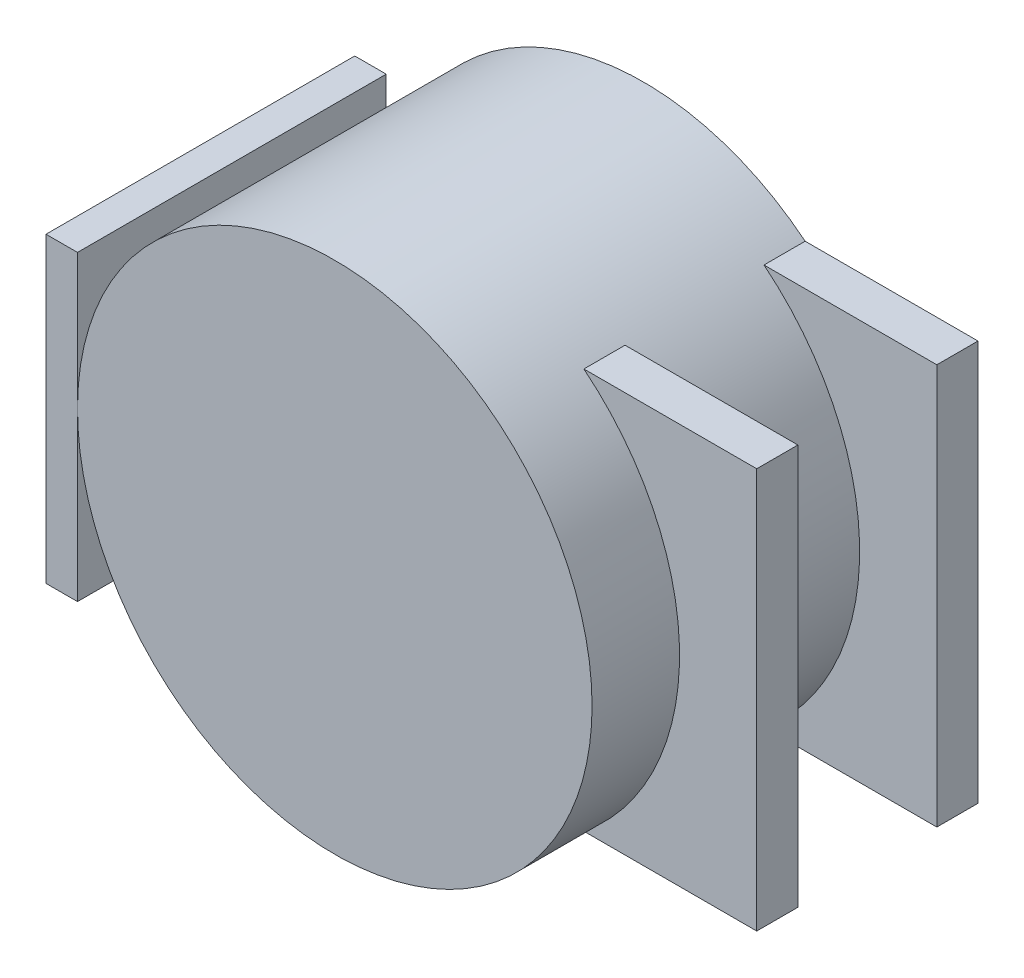
SolidWorks part; units mm, degrees
ref_plane "前视基准面" through (0, 0, 0) normal (0, 0, 1) x (1, 0, 0)
ref_plane "上视基准面" through (0, 0, 0) normal (0, 1, 0) x (1, 0, 0)
ref_plane "右视基准面" through (0, 0, 0) normal (1, 0, 0) x (0, 0, -1)
other "Configuration Table"
sketch "草图1" plane through (0, 0, 0) normal (0, 0, 1) x (1, 0, 0)
  circle A0 centre (0, 0) radius 5
extrude "凸台-拉伸1" add sketch "草图1" along normal blind 6
sketch "草图2" plane through (0, 0, 0) normal (0, 0, -1) x (-1, 0, 0)
  line L0 (5, 4.2787) -> (5, -4.2787) construction
  line L2 (5, 2.6314) -> (5.6118, 2.6314)
  line L3 (5, 2.6314) -> (5, -3.2456)
  line L4 (5, -3.2456) -> (5.6118, -3.2456)
  line L5 (5.6118, 2.6314) -> (5.6118, -3.2456)
  point P3 (5, 0)
extrude "凸台-拉伸2" add sketch "草图2" against normal blind 6 separate body
ref_plane "基准面1" through (0, 0, 0) normal (1, 0, 0) x (0, 0, -1)
sketch "草图3" plane through (0, 0, 0) normal (1, 0, 0) x (0, 0, -1)
  line L0 (0, -5) -> (0, 5) construction
  line L1 (0, 3.8902) -> (-0.8, 3.8902)
  line L2 (0, 3.8902) -> (0, -3.8902)
  line L3 (0, -3.8902) -> (-0.8, -3.8902)
  line L4 (-0.8, 3.8902) -> (-0.8, -3.8902)
extrude "凸台-拉伸3" add sketch "草图3" along normal blind 6.5
pattern_linear "阵列(线性)1" count 2 spacing 3.5 along (0, 0, 1) of "凸台-拉伸3"
